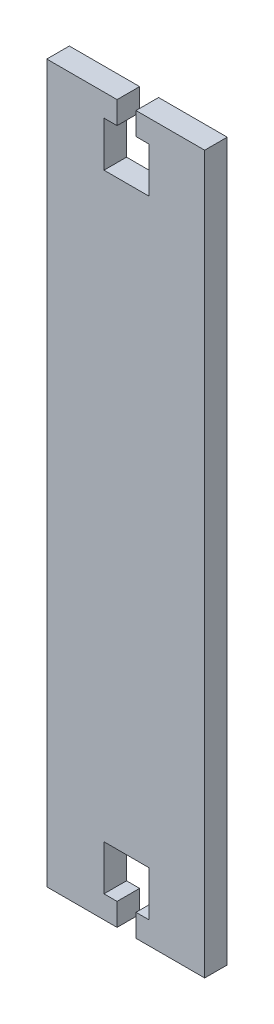
SolidWorks part; units mm, degrees
ref_plane "Plan de face" through (0, 0, 0) normal (0, 0, 1) x (1, 0, 0)
ref_plane "Plan de dessus" through (0, 0, 0) normal (0, 1, 0) x (1, 0, 0)
ref_plane "Plan de droite" through (0, 0, 0) normal (1, 0, 0) x (0, 0, -1)
sketch "Esquisse1" plane through (0, 0, 0) normal (0, 0, 1) x (1, 0, 0)
  line L0 (17.68, 160) -> (17.68, 20) construction
  line L1 (0, 0) -> (15.58, 0)
  line L2 (0, 0) -> (0, 158.92)
  line L3 (0, 158.92) -> (15.58, 158.92)
  line L4 (35, 0) -> (35, 158.92)
  line L9 (15.58, 0) -> (15.58, 5)
  line L21 (17.68, 0) -> (17.68, -42.5792) construction
  line L22 (19.78, 0) -> (35, 0)
  line L25 (0, 79.46) -> (64.0001, 79.46) construction
  line L27 (15.58, 158.92) -> (15.58, 153.92)
  line L37 (19.78, 158.92) -> (35, 158.92)
  line L38 (15.58, 153.92) -> (12.68, 153.92)
  line L39 (12.68, 153.92) -> (12.68, 143.92)
  line L40 (12.68, 143.92) -> (22.68, 143.92)
  line L45 (12.68, 15) -> (22.68, 15)
  line L46 (12.68, 5) -> (12.68, 15)
  line L47 (15.58, 5) -> (12.68, 5)
  line L48 (22.68, 143.92) -> (22.68, 153.92)
  line L49 (22.68, 153.92) -> (19.78, 153.92)
  line L50 (19.78, 153.92) -> (19.78, 158.92)
  line L51 (22.68, 15) -> (22.68, 5)
  line L52 (22.68, 5) -> (19.78, 5)
  line L53 (19.78, 5) -> (19.78, 0)
  dimension "D1" = 35
  dimension "D2" = 158.92
  dimension "D3" = 5
  dimension "D5" = 2.9
  dimension "D8" = 10
  dimension "D9" = 10
extrude "Boss.-Extru.2" add sketch "Esquisse1" along normal blind 5
